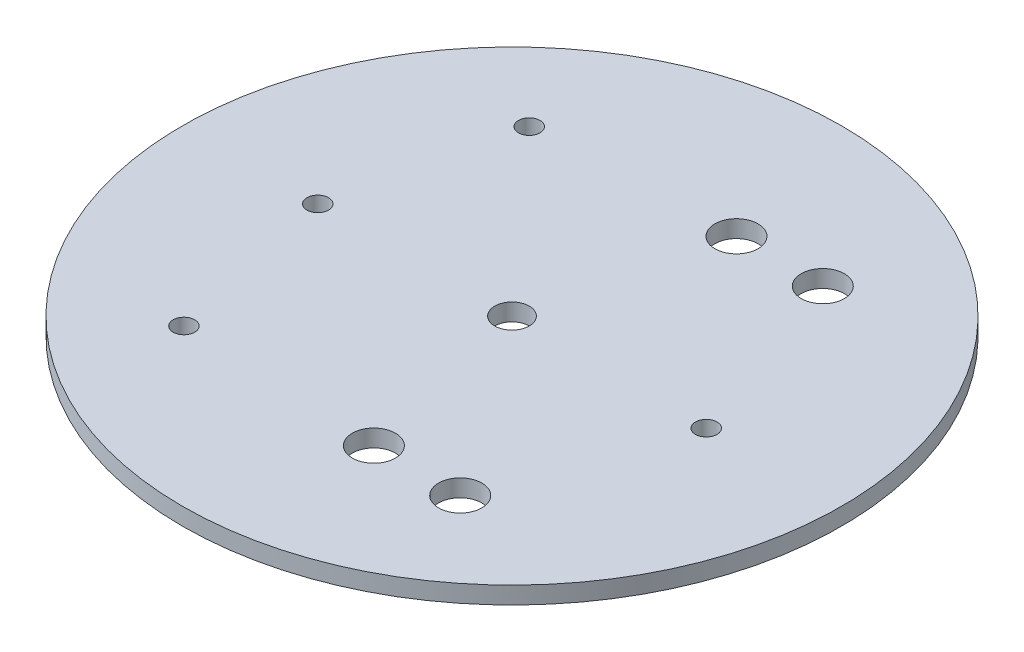
SolidWorks part; units mm, degrees
material "1060 Alloy"
ref_plane "Front Plane" through (0, 0, 0) normal (0, 0, 1) x (1, 0, 0)
ref_plane "Top Plane" through (0, 0, 0) normal (0, 1, 0) x (1, 0, 0)
ref_plane "Right Plane" through (0, 0, 0) normal (1, 0, 0) x (0, 0, -1)
sketch "Sketch1" plane through (0, 0, 0) normal (0, 1, 0) x (1, 0, 0)
  line L0 (45, 0) -> (-45, 0) construction
  line L1 (0, -45) -> (0, 0) construction
  line L2 (30, 42) -> (10, 42) construction
  circle A0 centre (0, 0) radius 76.35
  circle A1 centre (-45, 0) radius 2.5
  circle A2 centre (45, 0) radius 2.5
  circle A3 centre (0, 0) radius 4
  circle A6 centre (-36, 40) radius 2.5
  circle A7 centre (10, 42) radius 5
  circle A9 centre (30, 42) radius 5
  circle A10 centre (30, -42) radius 5
  circle A11 centre (10, -42) radius 5
  circle A12 centre (-36, -40) radius 2.5
  point P6 (0, 0)
  dimension "D1" = 152.7
  dimension "D2" = 5
  dimension "D3" = 5
  dimension "D5" = 8
  dimension "D6" = 20
  dimension "D8" = 10
  dimension "D9" = 10
  dimension "D10" = 5
  dimension "D4" = 90
  dimension "D7" = 45
  dimension "D11" = 40
  dimension "D12" = 36
  dimension "D13" = 42
  dimension "D14" = 10
extrude "Boss-Extrude1" add sketch "Sketch1" along normal blind 4
